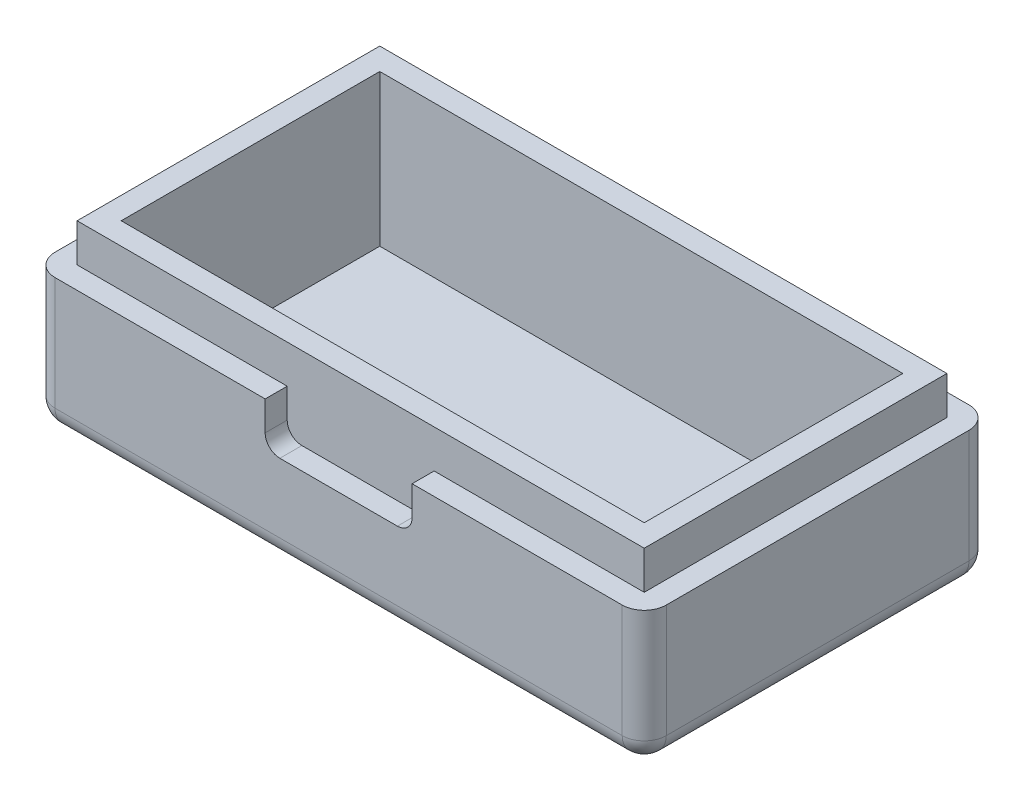
SolidWorks part; units mm, degrees
ref_plane "Front Plane" through (0, 0, 0) normal (0, 0, 1) x (1, 0, 0)
ref_plane "Top Plane" through (0, 0, 0) normal (0, 1, 0) x (1, 0, 0)
ref_plane "Right Plane" through (0, 0, 0) normal (1, 0, 0) x (0, 0, -1)
sketch "Sketch1" plane through (0, 0, 0) normal (0, 1, 0) x (1, 0, 0)
  line L1 (0, 0) -> (41.6, 0)
  line L2 (0, 0) -> (0, 23.6)
  line L3 (0, 23.6) -> (41.6, 23.6)
  line L4 (41.6, 0) -> (41.6, 23.6)
  dimension "D1" = 41.6
  dimension "D2" = 23.6
extrude "Boss-Extrude1" add sketch "Sketch1" along normal blind 11.8
sketch "Sketch2" plane through (0, 11.8, 0) normal (0, 1, 0) x (1, 0, 0)
  line L0 (20.8, 23.6) -> (20.8, 0) construction
  line L1 (41.6, 23.6) -> (0, 23.6) construction
  line L2 (0, 0) -> (41.6, 0) construction
  line L4 (3, 3) -> (38.6, 3)
  line L5 (3, 3) -> (3, 20.6)
  line L6 (3, 20.6) -> (38.6, 20.6)
  line L7 (38.6, 3) -> (38.6, 20.6)
  line L8 (3, 3) -> (38.6, 20.6) construction
  line L9 (3, 20.6) -> (38.6, 3) construction
  point P6 (20.8, 11.8)
  dimension "D1" = 17.6
  dimension "D2" = 35.6
extrude "Cut-Extrude1" cut sketch "Sketch2" against normal blind 10.3
sketch "Sketch4" plane through (0, 11.8, 0) normal (0, 1, 0) x (1, 0, 0)
  line L1 (0, 23.6) -> (41.6, 23.6)
  line L2 (0, 23.6) -> (0, 0)
  line L3 (0, 0) -> (41.6, 0)
  line L4 (41.6, 23.6) -> (41.6, 0)
  line L5 (1.5, 22.1) -> (40.1, 22.1)
  line L6 (1.5, 22.1) -> (1.5, 1.5)
  line L7 (1.5, 1.5) -> (40.1, 1.5)
  line L8 (40.1, 22.1) -> (40.1, 1.5)
  dimension "D1" = 1.5
  dimension "D2" = 1.5
  dimension "D3" = 1.5
  dimension "D4" = 1.5
extrude "Cut-Extrude2" cut sketch "Sketch4" against normal blind 2.6
fillet "Fillet1" radius 1.5 8 edges at (0, 4.6, 0) (0, 0, -11.8) (0, 4.6, -23.6) (41.6, 0, -11.8) (20.8, 0, -23.6) (20.8, 0, 0) (41.6, 4.6, -23.6) (41.6, 4.6, 0)
sketch "Sketch5" plane through (0, 0, -23.6) normal (0, 0, -1) x (-1, 0, 0)
  line L0 (-20.8, 6.2) -> (-20.8, 1.5) construction
  line L1 (-25.8, 9.2) -> (-15.8, 9.2)
  line L2 (-25.8, 9.2) -> (-25.8, 7.2)
  line L3 (-24.8, 6.2) -> (-16.8, 6.2)
  line L4 (-15.8, 9.2) -> (-15.8, 7.2)
  line L5 (-40.1, 1.5) -> (-1.5, 1.5) construction
  line L6 (-40.1, 9.2) -> (-1.5, 9.2) construction
  arc A0 (-16.8, 6.2) -> (-15.8, 7.2) centre (-16.8, 7.2) ccw
  arc A1 (-25.8, 7.2) -> (-24.8, 6.2) centre (-24.8, 7.2) ccw
  point P12 (-15.8, 6.2)
  dimension "D3" = 1
  dimension "D1" = 10
  dimension "D2" = 3
extrude "Cut-Extrude3" cut sketch "Sketch5" against normal up to surface (1.5 mm away) up to face at (20.8, 10.5, -22.1)
sketch "Sketch6" plane through (0, 0, 0) normal (0, 0, 1) x (1, 0, 0)
  line L0 (25.8, 9.2) -> (25.8, 7.2) construction
  line L1 (15.8, 9.2) -> (25.8, 9.2)
  line L2 (15.8, 9.2) -> (15.8, 7.2)
  line L3 (16.8, 6.2) -> (24.8, 6.2)
  line L4 (25.8, 9.2) -> (25.8, 7.2)
  line L5 (24.8, 6.2) -> (16.8, 6.2) construction
  arc A0 (24.8, 6.2) -> (25.8, 7.2) centre (24.8, 7.2) ccw
  arc A1 (15.8, 7.2) -> (16.8, 6.2) centre (16.8, 7.2) ccw
  point P11 (25.8, 6.2)
  dimension "D1" = 1
extrude "Cut-Extrude4" cut sketch "Sketch6" against normal up to surface (1.5 mm away) up to face at (20.8, 10.5, -1.5)
ref_plane "Plane1" through (1.5, 11.8, -1.5) normal (0, 0, 1) x (1, 0, 0)
